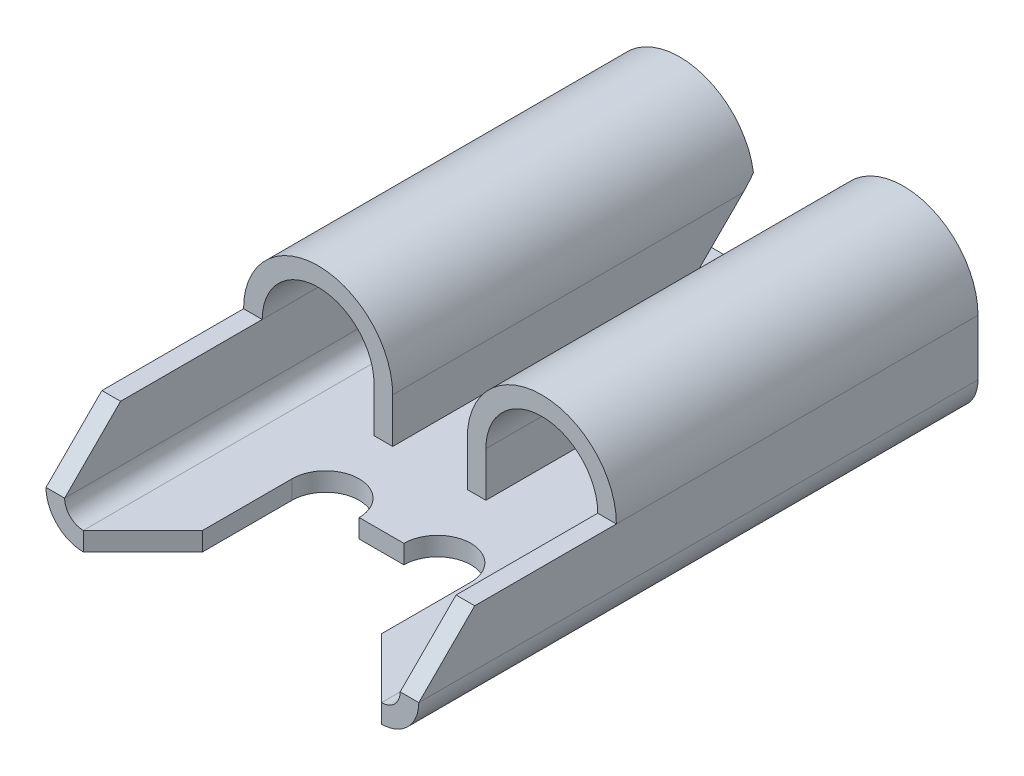
SolidWorks part; units mm, degrees
material "Duranickel(R) 301"
ref_plane "Front Plane" through (0, 0, 0) normal (0, 0, 1) x (1, 0, 0)
ref_plane "Top Plane" through (0, 0, 0) normal (0, 1, 0) x (1, 0, 0)
ref_plane "Right Plane" through (0, 0, 0) normal (1, 0, 0) x (0, 0, -1)
sketch "Sketch1" plane through (0, 0, 0) normal (0, 0, 1) x (1, 0, 0)
  line L0 (0, 0) -> (-4, 0)
  line L1 (-5, 1) -> (-5, 2.5)
  line L2 (-3, 4.5) -> (-6.9924, 4.5) construction
  line L3 (-1, 2.5) -> (-1, 1.3)
  line L4 (-3, 4.5) -> (-3, 1.4997) construction
  line L5 (-1.9949, 2.5) -> (-4.1903, 2.5) construction
  line L6 (0, 0.5) -> (-4, 0.5)
  line L7 (-4.5, 1) -> (-4.5, 2.5)
  line L8 (-1.5, 2.5) -> (-1.5, 1.3)
  line L9 (-1.5, 1.3) -> (-1, 1.3)
  line L10 (0, 0) -> (0, 8.3351) construction
  line L11 (1.9949, 2.5) -> (4.1903, 2.5) construction
  line L12 (3, 4.5) -> (3, 1.4997) construction
  line L13 (3, 4.5) -> (6.9924, 4.5) construction
  line L14 (1.5, 1.3) -> (1, 1.3)
  line L15 (1.5, 2.5) -> (1.5, 1.3)
  line L16 (4.5, 1) -> (4.5, 2.5)
  line L17 (0, 0.5) -> (4, 0.5)
  line L18 (1, 2.5) -> (1, 1.3)
  line L19 (5, 1) -> (5, 2.5)
  line L20 (0, 0) -> (4, 0)
  arc A0 (-1, 2.5) -> (-5, 2.5) centre (-3, 2.5) ccw
  arc A1 (-4, 0) -> (-5, 1) centre (-4, 1) cw
  arc A2 (-4, 0.5) -> (-4.5, 1) centre (-4, 1) cw
  arc A3 (-1.5, 2.5) -> (-4.5, 2.5) centre (-3, 2.5) ccw
  arc A4 (1.5, 2.5) -> (4.5, 2.5) centre (3, 2.5) cw
  arc A5 (4, 0.5) -> (4.5, 1) centre (4, 1) ccw
  arc A6 (4, 0) -> (5, 1) centre (4, 1) ccw
  arc A7 (1, 2.5) -> (5, 2.5) centre (3, 2.5) cw
  point P0 (5, 0)
  point P14 (-5, 0)
  dimension "D3" = 2
  dimension "D5" = 1
  dimension "D1" = 4.5
  dimension "D2" = 5
  dimension "D4" = 4
  dimension "D6" = 0.8
  dimension "D7" = 0.5
extrude "Boss-Extrude1" add sketch "Sketch1" against normal blind 15
sketch "Sketch2" plane through (0, 0, 0) normal (0, -1, 0) x (1, 0, 0)
  line L0 (-4, 0) -> (-2.4, -1.6)
  line L1 (-4, 0) -> (4, 0) construction
  line L2 (-2.4, -1.6) -> (-2.4, -4)
  line L3 (-0.6, -4) -> (0.6, -4)
  line L4 (0, 0) -> (0, -16.3705) construction
  line L5 (-4, 0) -> (-4, 0.5375)
  line L6 (-4, 0.5375) -> (4, 0.5375)
  line L7 (0, 0.5375) -> (0, -4) construction
  line L8 (-5, -15) -> (-5, 0) construction
  line L9 (4, 0) -> (4, 0.5375)
  line L10 (2.4, -1.6) -> (2.4, -4)
  line L11 (4, 0) -> (2.4, -1.6)
  arc A0 (-2.4, -4) -> (-0.6, -4) centre (-1.5, -4) ccw
  arc A1 (2.4, -4) -> (0.6, -4) centre (1.5, -4) cw
  dimension "D1" = 0.6
  dimension "D2" = 45
  dimension "D3" = 4
  dimension "D4" = 2.6
  dimension "D5" = 1
extrude "Cut-Extrude1" cut sketch "Sketch2" against normal through all
sketch "Sketch3" plane through (0, 0, 0) normal (0, -1, 0) x (1, 0, 0)
  line L0 (5, -15) -> (5, 0) construction
  line L1 (-5, 0) -> (5, 0)
  line L2 (-5, 0) -> (-5, -5.3)
  line L3 (-5, -5.3) -> (5, -5.3)
  line L4 (5, 0) -> (5, -5.3)
  line L5 (-4, -15) -> (4, -15) construction
  dimension "D1" = 9.7
extrude "Cut-Extrude2" cut sketch "Sketch3" along normal blind 2 from offset 4.5 offset against normal yes
sketch "Sketch4" plane through (0, 2.5, 0) normal (0, 1, 0) x (1, 0, 0)
  line L1 (-1.5, 5.3) -> (1.5, 5.3)
  line L2 (-1.5, 5.3) -> (-1.5, 4.4844)
  line L3 (-1.5, 4.4844) -> (1.5, 4.4844)
  line L4 (1.5, 5.3) -> (1.5, 4.4844)
  dimension "D1" = 3
extrude "Cut-Extrude3" cut sketch "Sketch4" against normal up to surface (2 mm away) up to face at (0, 0.5, -5.1)
chamfer "Chamfer1" distance 1.5 angle 45 4 edges at (4.75, 2.5, 0) (-4.75, 2.5, 0) (1.25, 1.3, -15) (-1.25, 1.3, -15)
